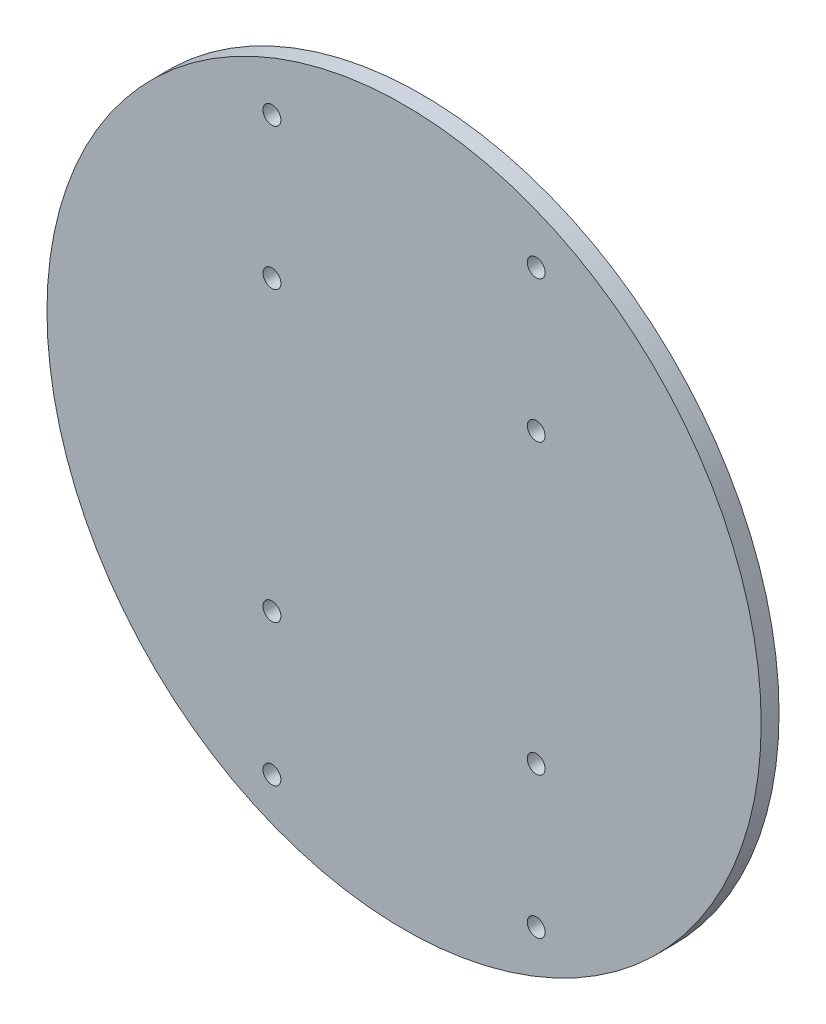
SolidWorks part; units mm, degrees
ref_plane "Alzado" through (0, 0, 0) normal (0, 0, 1) x (1, 0, 0)
ref_plane "Planta" through (0, 0, 0) normal (0, 1, 0) x (1, 0, 0)
ref_plane "Vista lateral" through (0, 0, 0) normal (1, 0, 0) x (0, 0, -1)
sketch "Croquis1" plane through (0, 0, 0) normal (0, 0, 1) x (1, 0, 0)
  circle A0 centre (0, 0) radius 82.42
  dimension "D1" = 164.84
extrude "Saliente-Extruir1" add sketch "Croquis1" along normal blind 5
sketch "Croquis2" plane through (0, 0, 5) normal (0, 0, 1) x (1, 0, 0)
  circle A1 centre (0, 0) radius 100
  dimension "D1" = 200
extrude "Saliente-Extruir2" add sketch "Croquis2" against normal up to surface (5 mm away) up to face at (82.42, 0, 0)
sketch "Croquis3" plane through (0, 0, 5) normal (0, 0, 1) x (1, 0, 0)
  line L0 (0, -80.9032) -> (-37, -80.9032) construction
  line L1 (0, 0) -> (0, 12.3418) construction
  line L2 (0, 100) -> (0, -100) construction
  line L3 (0, 0) -> (-100, 0) construction
  line L4 (0, 0) -> (100, 0) construction
  line L5 (0, -80.9032) -> (37, -80.9032) construction
  line L6 (-37, -80.9032) -> (-37, -92.9032) construction
  line L7 (-37, -80.9032) -> (-43, -80.9032) construction
  line L8 (-37, -80.9032) -> (-37, -41.3032) construction
  line L9 (-37, -41.3032) -> (37, -41.3032) construction
  circle A1 centre (0, 0) radius 100 construction
  circle A2 centre (-37, -80.9032) radius 2.5
  circle A3 centre (37, -80.9032) radius 2.5
  circle A4 centre (-37, -41.3032) radius 2.5
  circle A5 centre (37, -41.3032) radius 2.5
  dimension "D1" = 37
  dimension "D3" = 5
  dimension "D4" = 5
  dimension "D5" = 12
  dimension "D8" = 5
  dimension "D10" = 5
  dimension "D2" = 37
  dimension "D6" = 6
  dimension "D7" = 39.6
  dimension "D9" = 74
extrude "Cortar-Extruir1" cut sketch "Croquis3" against normal blind 10
sketch "Croquis4" plane through (0, 0, 5) normal (0, 0, 1) x (1, 0, 0)
  line L0 (-37, -41.3032) -> (-37, -35.3032) construction
  line L1 (-37, -35.3032) -> (-37, 33.4468) construction
  line L2 (-37, 33.4468) -> (-37, 39.4468) construction
  line L3 (-37, 39.4468) -> (-37, 79.0468) construction
  line L4 (-37, 79.0468) -> (37, 79.0468) construction
  line L5 (37, 79.0468) -> (37, 39.4468) construction
  line L6 (37, 39.4468) -> (-37, 39.4468) construction
  circle A0 centre (-37, -41.3032) radius 2.5
  circle A1 centre (-37, 39.4468) radius 2.5
  circle A2 centre (-37, -80.9032) radius 2.5
  circle A3 centre (-37, 79.0468) radius 2.5
  circle A4 centre (37, -41.3032) radius 2.5
  circle A5 centre (37, 79.0468) radius 2.5
  circle A6 centre (37, 39.4468) radius 2.5
  dimension "D4" = 5
  dimension "D6" = 5
  dimension "D8" = 5
  dimension "D9" = 5
  dimension "D1" = 6
  dimension "D2" = 68.75
  dimension "D3" = 6
  dimension "D5" = 39.6
  dimension "D7" = 74
extrude "Cortar-Extruir2" cut sketch "Croquis4" against normal blind 10
